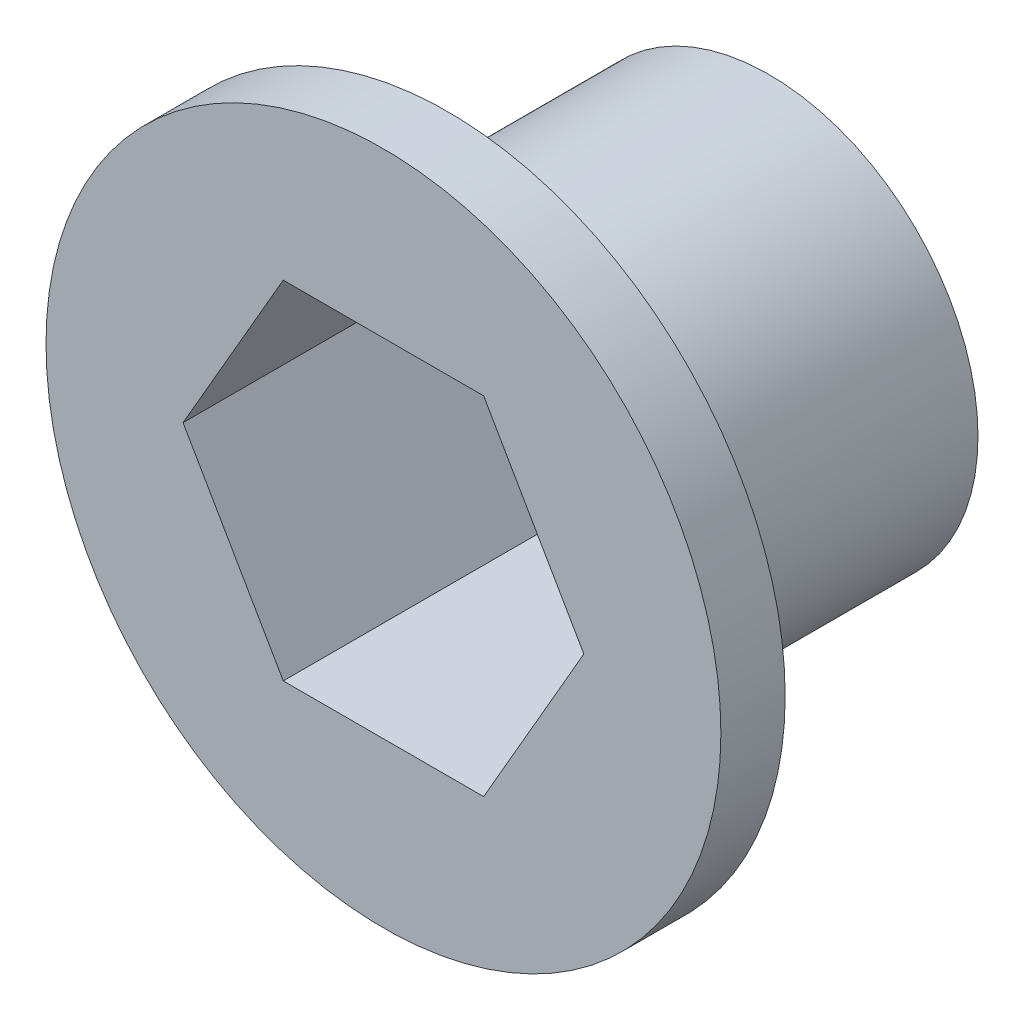
SolidWorks part; units mm, degrees
ref_plane "Front Plane" through (0, 0, 0) normal (0, 0, 1) x (1, 0, 0)
ref_plane "Top Plane" through (0, 0, 0) normal (0, 1, 0) x (1, 0, 0)
ref_plane "Right Plane" through (0, 0, 0) normal (1, 0, 0) x (0, 0, -1)
sketch "Sketch1" plane through (0, 0, 0) normal (0, 0, 1) x (1, 0, 0)
  line L1 (3.1177, 0) -> (1.5588, 2.7)
  line L2 (1.5588, 2.7) -> (-1.5588, 2.7)
  line L3 (-1.5588, 2.7) -> (-3.1177, 0)
  line L4 (-3.1177, 0) -> (-1.5588, -2.7)
  line L5 (-1.5588, -2.7) -> (1.5588, -2.7)
  line L6 (1.5588, -2.7) -> (3.1177, 0)
  circle A0 centre (0, 0) radius 2.7 construction
  circle A1 centre (0, 0) radius 3.25
  dimension "D1" = 5.4
  dimension "D2" = 6.5
extrude "Boss-Extrude1" add sketch "Sketch1" along normal mid plane 5
sketch "Sketch2" plane through (0, 0, 2.5) normal (0, 0, 1) x (1, 0, 0)
  line L0 (1.5588, -2.7) -> (3.1177, 0) construction
  line L1 (3.1177, 0) -> (1.5588, 2.7)
  line L2 (1.5588, 2.7) -> (-1.5588, 2.7)
  line L3 (-1.5588, 2.7) -> (-3.1177, 0)
  line L4 (-3.1177, 0) -> (-1.5588, -2.7)
  line L5 (-1.5588, -2.7) -> (1.5588, -2.7)
  line L6 (1.5588, -2.7) -> (3.1177, 0)
  circle A0 centre (0, 0) radius 5.25
  circle A1 centre (0, 0) radius 3.25 construction
  circle A3 centre (0, 0) radius 2.7 construction
  point P4 (2.9594, -0.2742)
  point P15 (3.1192, 0)
  dimension "D1" = 2
extrude "Boss-Extrude2" add sketch "Sketch2" along normal blind 1
